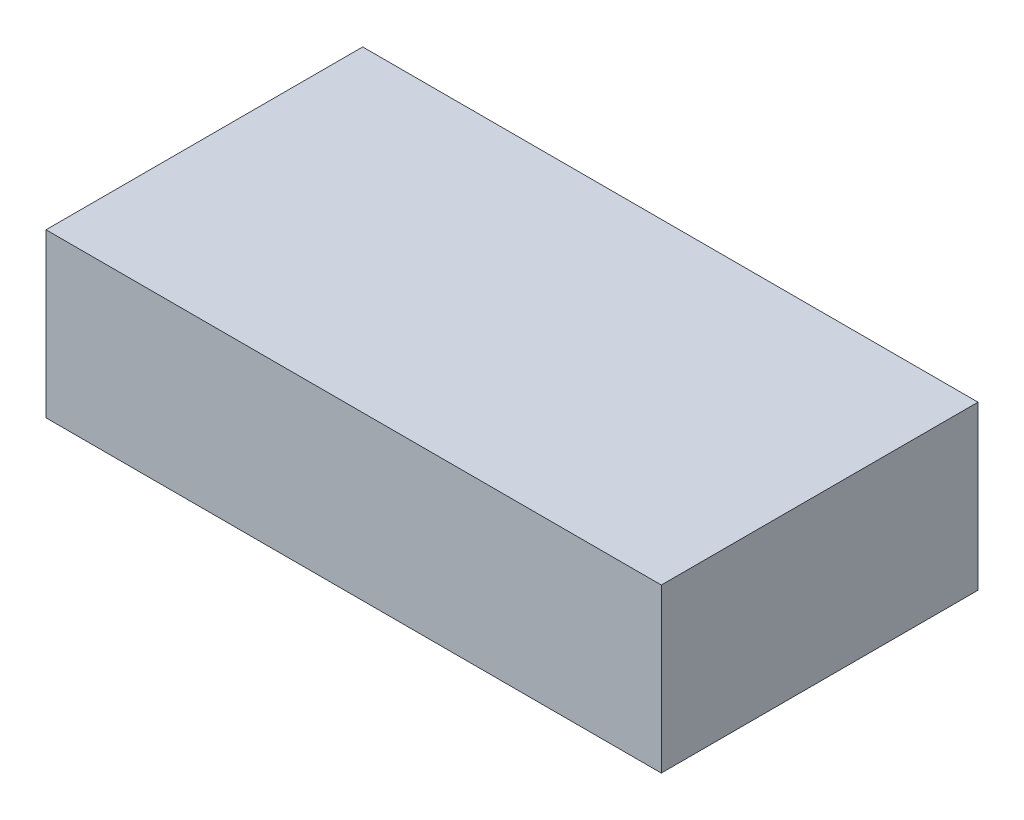
SolidWorks part; units mm, degrees
ref_plane "Front Plane" through (0, 0, 0) normal (0, 0, 1) x (1, 0, 0)
ref_plane "Top Plane" through (0, 0, 0) normal (0, 1, 0) x (1, 0, 0)
ref_plane "Right Plane" through (0, 0, 0) normal (1, 0, 0) x (0, 0, -1)
sketch "Sketch1" plane through (0, 0, 0) normal (0, 1, 0) x (1, 0, 0)
  line L1 (-34, 17.5) -> (34, 17.5)
  line L2 (-34, 17.5) -> (-34, -17.5)
  line L3 (-34, -17.5) -> (34, -17.5)
  line L4 (34, 17.5) -> (34, -17.5)
  dimension "D1" = 35
  dimension "D2" = 68
  dimension "D3" = 34
  dimension "D4" = 17.5
extrude "Boss-Extrude1" add sketch "Sketch1" along normal blind 18
